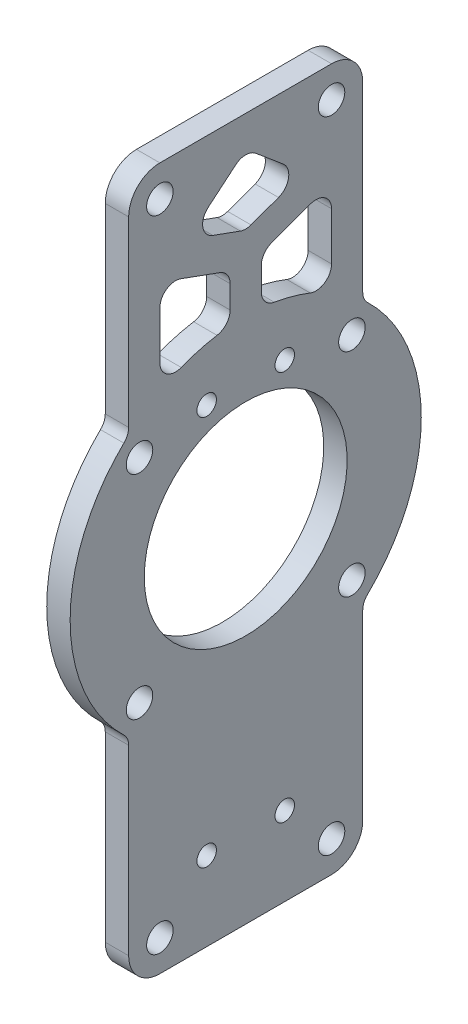
SolidWorks part; units mm, degrees
material "Сплав 2024"
ref_plane "Спереди" through (0, 0, 0) normal (0, 0, 1) x (1, 0, 0)
ref_plane "Сверху" through (0, 0, 0) normal (0, 1, 0) x (1, 0, 0)
ref_plane "Справа" through (0, 0, 0) normal (1, 0, 0) x (0, 0, -1)
sketch "Эскиз1" plane through (0, 0, 0) normal (0, 1, 0) x (1, 0, 0)
  line L1 (0, 0) -> (3, 0)
  line L2 (0, 0) -> (0, -30)
  line L3 (0, -30) -> (3, -30)
  line L4 (3, 0) -> (3, -30)
  dimension "D1" = 3
  dimension "D2" = 30
extrude "Бобышка-Вытянуть1" add sketch "Эскиз1" along normal blind 90
sketch "Эскиз2" plane through (0, 0, 0) normal (-1, 0, 0) x (0, 0, 1)
  line L0 (30, 45) -> (0, 45) construction
  line L1 (30, 90) -> (30, 0) construction
  line L2 (0, 90) -> (0, 0) construction
  line L3 (15, 90) -> (15, 0) construction
  line L4 (0, 90) -> (30, 90) construction
  line L5 (0, 0) -> (30, 0) construction
  circle A0 centre (15, 45) radius 22.5
  point P2 (30, 45)
  point P3 (0, 45)
  dimension "D1" = 45
extrude "Бобышка-Вытянуть2" add sketch "Эскиз2" against normal up to surface (3 mm away) up to face at (3, 45, 15)
sketch "Эскиз3" plane through (0, 0, 0) normal (-1, 0, 0) x (0, 0, 1)
  circle A0 centre (15, 45) radius 13
  dimension "D1" = 26
extrude "Вырез-Вытянуть1" cut sketch "Эскиз3" against normal through all
sketch "Эскиз4" plane through (3, 0, 0) normal (-1, 0, 0) x (0, 0, 1)
  line L0 (30.9099, 60.9099) -> (-0.9099, 29.0901) construction
  line L2 (30.9099, 29.0901) -> (-0.9099, 60.9099) construction
  line L3 (30, 45) -> (0, 45) construction
  circle A0 centre (15, 45) radius 19.25 construction
  circle A1 centre (15, 45) radius 22.5 construction
  dimension "D1" = 38.5
  dimension "D2" = 45
hole_wizard "Отверстие с зазором M31" positions "Эскиз6" profile "Эскиз5" hole size "M3" standard "Ansi Metric" end condition through all
sketch "Эскиз6" plane through (3, -25.0247, 7.2629) normal (-1, 0, 0) x (0, 0, 1)
  line L0 (23.647, 85.9346) -> (-8.1728, 54.1148) construction
  line L1 (23.647, 54.1148) -> (-8.1728, 85.9346) construction
  circle A0 centre (7.7371, 70.0247) radius 19.25 construction
  point P0 (21.3489, 83.6365)
  point P6 (-5.8747, 83.6365)
  point P10 (-5.8747, 56.4129)
  point P12 (21.3489, 56.4129)
sketch "Эскиз5" plane through (3, 58.6118, 28.6118) normal (0, 1, 0) x (0, 0, -1)
  line L0 (0, 0) -> (0, 3)
  line L1 (0, 3) -> (1.7, 3)
  line L2 (1.7, 3) -> (1.7, 0)
  line L5 (1.7, 0) -> (0, 0)
  line L11 (0, -6.35) -> (0, 107.95) construction
  dimension "Диаметр сквозного отверстия" = 3.4
  dimension "Глубина сквозного отверстия" = 3
sketch "Эскиз8" plane through (3, 0, 0) normal (1, 0, 0) x (0, 0, -1)
  line L0 (-15, 90) -> (-15, 0) construction
  line L1 (-30, 90) -> (0, 90) construction
  line L2 (-30, 0) -> (0, 0) construction
  line L3 (19.447, 45) -> (-49.447, 45) construction
  line L4 (0, 90) -> (0, 61.7705) construction
  line L5 (-26, 86) -> (-4, 86) construction
  line L6 (-26, 86) -> (-26, 4) construction
  line L7 (-26, 4) -> (-4, 4) construction
  line L8 (-4, 86) -> (-4, 4) construction
  line L9 (-26, 86) -> (-4, 4) construction
  line L10 (-26, 4) -> (-4, 86) construction
  line L11 (0, 0) -> (-30, 0) construction
  point P8 (-15, 45)
  point P9 (-15, 45)
  dimension "D1" = 4
  dimension "D2" = 4
  dimension "D3" = 82
  dimension "D4" = 22
hole_wizard "Отверстие с зазором M32" positions "Эскиз10" profile "Эскиз9" hole size "M3" standard "Ansi Metric" end condition through all
sketch "Эскиз10" plane through (3, 0, 0) normal (1, 0, 0) x (0, 0, -1)
  point P0 (-26, 86)
  point P3 (-4, 86)
  point P6 (-4, 4)
  point P9 (-26, 4)
sketch "Эскиз9" plane through (3, 86, 26) normal (0, 1, 0) x (0, 0, -1)
  line L0 (0, 0) -> (0, 3)
  line L1 (0, 3) -> (1.7, 3)
  line L2 (1.7, 3) -> (1.7, 0)
  line L5 (1.7, 0) -> (0, 0)
  line L11 (0, -6.35) -> (0, 107.95) construction
  dimension "Диаметр сквозного отверстия" = 3.4
  dimension "Глубина сквозного отверстия" = 3
fillet "Скругление1" radius 4 4 edges at (1.5, 0, 0) (1.5, 0, 30) (1.5, 90, 30) (1.5, 90, 0)
sketch "Эскиз11" plane through (0, 0, 0) normal (1, 0, 0) x (0, 0, -1)
  line L0 (-30, 60.12) -> (0, 60.12) construction
  line L1 (-4, 0) -> (-26, 0) construction
  line L2 (0, 86) -> (0, 61.7705) construction
  line L3 (-20, 76) -> (-20, 0) construction
  line L5 (-10, 76) -> (-10, 0) construction
  line L6 (-35.3867, 10.12) -> (5.0681, 10.12) construction
  point P8 (-10, 60.12)
  point P17 (-20, 60.12)
  point P18 (-20, 10.12)
  point P19 (-10, 10.12)
  dimension "D1" = 10.12
  dimension "D2" = 10
  dimension "D3" = 10
  dimension "D4" = 50
hole_wizard "Отверстие обработанное метчиком M3x0.51" positions "Эскиз13" profile "Эскиз12" tap size "M3x0.5" standard "Ansi Metric" end condition up to next
sketch "Эскиз13" plane through (0, 0, 0) normal (-1, 0, 0) x (0, 0, 1)
  point P0 (10, 60.12)
  point P3 (20, 60.12)
  point P6 (10, 10.12)
  point P9 (20, 10.12)
sketch "Эскиз12" plane through (0, 60.12, 10) normal (0, 1, 0) x (0, 0, 1)
  line L0 (0, 0) -> (0, 3)
  line L1 (0, 3) -> (1.25, 3)
  line L2 (1.25, 3) -> (1.25, 0)
  line L5 (1.25, 0) -> (0, 0)
  line L11 (0, -6.35) -> (0, 107.95) construction
  dimension "Диаметр проходного сверла" = 2.5
  dimension "Глубина проходного сверла" = 3
cosmetic thread "Отверстие резьбы1" parameters "D2"=3
cosmetic thread "Отверстие резьбы2" parameters "D2"=3
cosmetic thread "Отверстие резьбы3" parameters "D2"=3
cosmetic thread "Отверстие резьбы4" parameters "D2"=3
sketch "Эскиз14" plane through (0, 0, 0) normal (-1, 0, 0) x (0, 0, 1)
  line L0 (4, 90) -> (4, 0) construction
  line L1 (4, 90) -> (26, 90) construction
  line L2 (4, 0) -> (26, 0) construction
  line L3 (26, 0) -> (26, 90) construction
  line L4 (0, 86) -> (0, 61.7705) construction
  line L5 (30, 86) -> (30, 61.7705) construction
  line L6 (0, 86) -> (30, 86) construction
  line L7 (13, 73.4942) -> (13, 67.4109)
  line L8 (17, 73.4942) -> (17, 67.4109)
  line L9 (15, 90) -> (15, 0) construction
  line L10 (17, 73.4942) -> (26, 76.7699)
  line L11 (26, 76.7699) -> (26, 64.6278)
  line L12 (13, 73.4942) -> (4, 76.7699)
  line L13 (4, 76.7699) -> (4, 64.6278)
  line L14 (7.5382, 79.7388) -> (15, 77.0229)
  line L15 (22.4618, 79.7388) -> (15, 77.0229)
  line L16 (4, 76.7699) -> (15, 86) construction
  line L17 (15, 86) -> (26, 76.7699) construction
  line L18 (7.5382, 79.7388) -> (15, 86)
  line L19 (15, 86) -> (22.4618, 79.7388)
  line L20 (0, 76.7699) -> (30, 76.7699) construction
  line L21 (4, 73.4942) -> (26, 73.4942) construction
  line L22 (15, 45) -> (37.5, 45) construction
  circle A0 centre (15, 45) radius 22.5 construction
  arc A1 (4, 64.6278) -> (13, 67.4109) centre (15, 45) cw
  arc A2 (17, 67.4109) -> (26, 64.6278) centre (15, 45) cw
  arc A3 (30, 28.2295) -> (30, 61.7705) centre (15, 45) ccw construction
  point P14 (4, 64.6278)
  point P15 (26, 64.6278)
  point P33 (15, 86)
  dimension "D4" = 4
  dimension "D1" = 4
  dimension "D2" = 4
  dimension "D3" = 4
  dimension "D5" = 2
  dimension "D6" = 110
  dimension "D7" = 110
  dimension "D8" = 100
  dimension "D9" = 4
extrude "Вырез-Вытянуть2" cut sketch "Эскиз14" against normal through all
fillet "Скругление2" radius 2 16 edges at (1.5, 64.6278, 26) (1.5, 67.4109, 17) (1.5, 64.6278, 4) (1.5, 67.4109, 13) (1.5, 73.4942, 17) (1.5, 76.7699, 4) (1.5, 79.7388, 7.5382) (1.5, 79.7388, 22.4618) (1.5, 77.0229, 15) (1.5, 73.4942, 13) (1.5, 76.7699, 26) (1.5, 86, 15) (1.5, 28.2295, 30) (1.5, 61.7705, 30) (1.5, 61.7705, 0) (1.5, 28.2295, 0)
